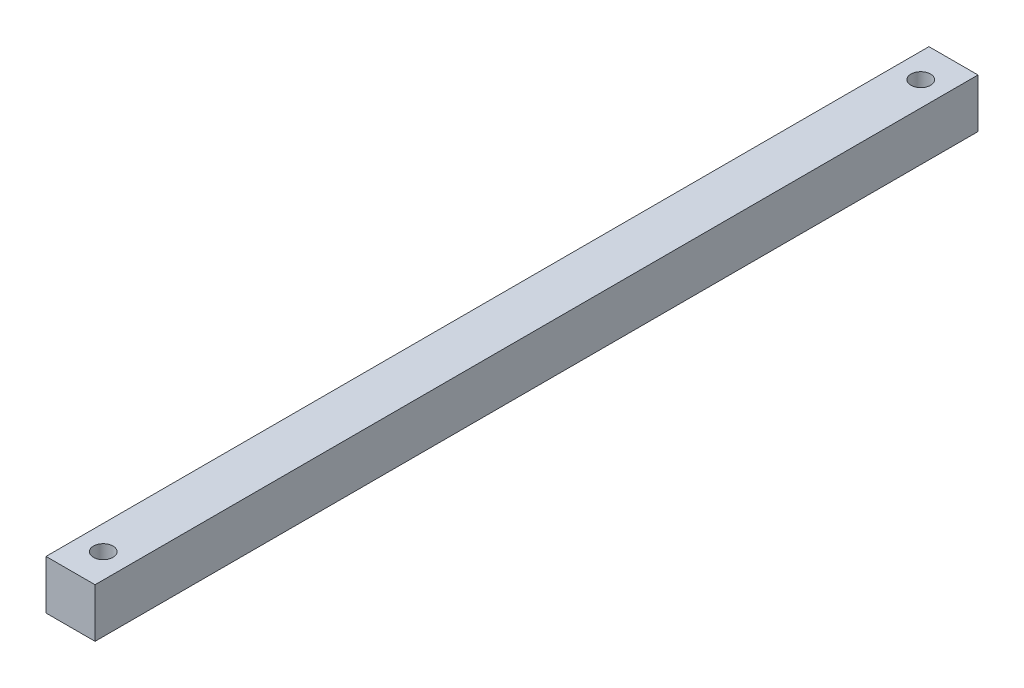
SolidWorks part; units mm, degrees
ref_plane "前视基准面" through (0, 0, 0) normal (0, 0, 1) x (1, 0, 0)
ref_plane "上视基准面" through (0, 0, 0) normal (0, 1, 0) x (1, 0, 0)
ref_plane "右视基准面" through (0, 0, 0) normal (1, 0, 0) x (0, 0, -1)
other "Configuration Table"
sketch "草图1" plane through (0, 0, 0) normal (0, 0, 1) x (1, 0, 0)
  line L1 (0, 0) -> (15, 0)
  line L2 (0, 0) -> (0, -15)
  line L3 (0, -15) -> (15, -15)
  line L4 (15, 0) -> (15, -15)
  dimension "D1" = 15
  dimension "D2" = 15
extrude "凸台-拉伸1" add sketch "草图1" along normal blind 270
sketch "草图2" plane through (0, 0, 0) normal (0, 1, 0) x (1, 0, 0)
  line L0 (7.5, 0) -> (7.5, -270) construction
  line L1 (15, 0) -> (0, 0) construction
  line L2 (15, -270) -> (0, -270) construction
  circle A0 centre (7.5, -10) radius 3
  circle A1 centre (7.5, -260) radius 3
  dimension "D3" = 6
  dimension "D4" = 6
  dimension "D1" = 250
  dimension "D2" = 10
extrude "切除-拉伸1" cut sketch "草图2" against normal through all
